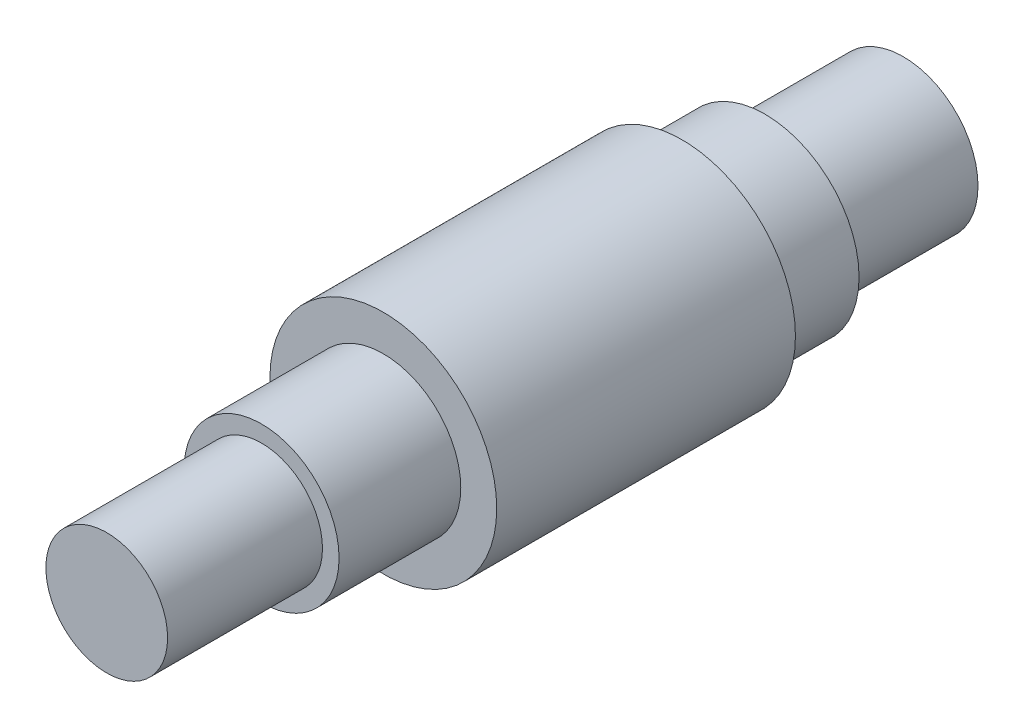
SolidWorks part; units mm, degrees
ref_plane "Front Plane" through (0, 0, 0) normal (0, 0, 1) x (1, 0, 0)
ref_plane "Top Plane" through (0, 0, 0) normal (0, 1, 0) x (1, 0, 0)
ref_plane "Right Plane" through (0, 0, 0) normal (1, 0, 0) x (0, 0, -1)
sketch "Sketch1" plane through (0, 0, 0) normal (1, 0, 0) x (0, 0, -1)
  line L1 (0, 0) -> (14, 0)
  line L2 (0, 0) -> (0, 5.5)
  line L3 (0, 5.5) -> (14, 5.5)
  line L4 (14, 0) -> (14, 5.5)
  line L5 (14, 0) -> (25, 0)
  line L6 (14, 0) -> (14, 7)
  line L7 (14, 7) -> (25, 7)
  line L8 (25, 0) -> (25, 7)
  line L9 (25, 0) -> (52, 0)
  line L10 (25, 0) -> (25, 10.25)
  line L11 (25, 10.25) -> (52, 10.25)
  line L12 (52, 0) -> (52, 10.25)
  line L13 (52, 0) -> (59.5, 0)
  line L14 (52, 0) -> (52, 8.5)
  line L15 (52, 8.5) -> (59.5, 8.5)
  line L16 (59.5, 0) -> (59.5, 8.5)
  line L17 (59.5, 0) -> (72, 0)
  line L18 (59.5, 0) -> (59.5, 6.75)
  line L19 (59.5, 6.75) -> (72, 6.75)
  line L20 (72, 0) -> (72, 6.75)
  dimension "D1" = 5.5
  dimension "D2" = 14
  dimension "D3" = 7
  dimension "D4" = 11
  dimension "D5" = 10.25
  dimension "D6" = 27
  dimension "D7" = 7.5
  dimension "D8" = 8.5
  dimension "D9" = 6.75
  dimension "D10" = 12.5
revolve "Revolve2" add sketch "Sketch1" angle 360 about L9
